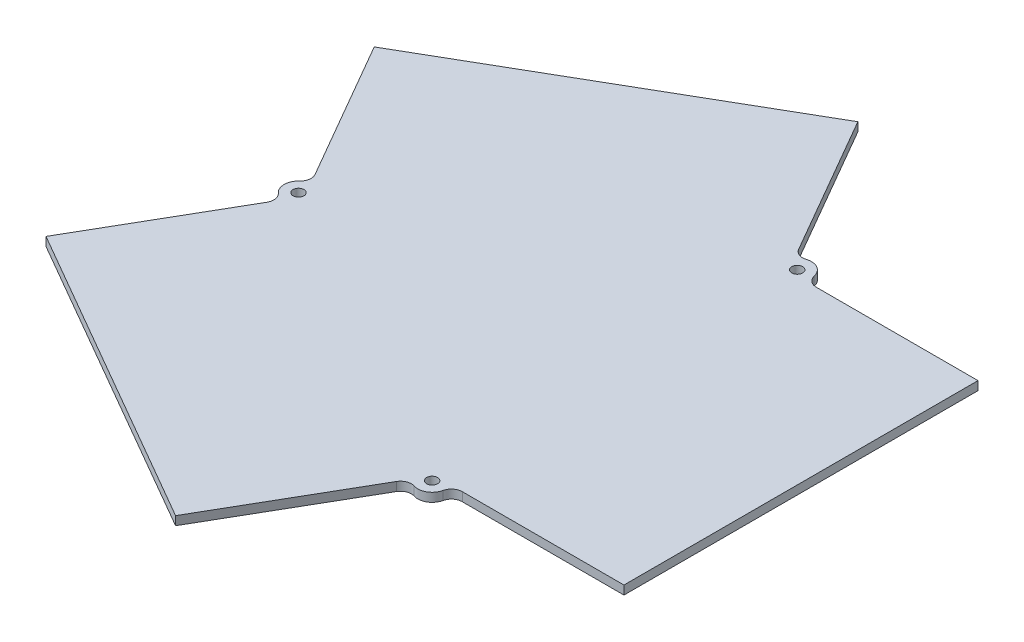
SolidWorks part; units mm, degrees
material "Acrylic (Medium-high impact)"
ref_plane "Front Plane" through (0, 0, 0) normal (0, 0, 1) x (1, 0, 0)
ref_plane "Top Plane" through (0, 0, 0) normal (0, 1, 0) x (1, 0, 0)
ref_plane "Right Plane" through (0, 0, 0) normal (1, 0, 0) x (0, 0, -1)
sketch "Sketch1" plane through (0, 0, 0) normal (0, 1, 0) x (1, 0, 0)
  line L0 (-80.9213, 31.2483) -> (-101.2337, 66.4304)
  line L1 (-103.9658, 67.1624) -> (-33.8177, 107.6624)
  line L2 (-33.8177, 107.6624) -> (-14.0109, 73.356)
  line L4 (-8.3973, 70.115) -> (31.2163, 70.115)
  line L5 (31.2163, 70.115) -> (31.2163, -10.885)
  line L6 (31.2163, -10.885) -> (-8.3973, -10.885)
  line L8 (-14.0109, -14.126) -> (-33.8177, -48.4324)
  line L9 (-33.8177, -48.4324) -> (-103.9658, -7.9324)
  line L10 (-103.9658, -7.9324) -> (-84.1589, 26.374)
  line L12 (-84.1589, 32.856) -> (-103.9658, 67.1624)
  line L13 (-101.2337, 66.4304) -> (-34.5498, 104.9304)
  line L14 (-34.5498, 104.9304) -> (-14.2374, 69.7483)
  line L15 (-11.4084, 68.115) -> (29.2163, 68.115)
  line L16 (29.2163, 68.115) -> (29.2163, -8.885)
  line L17 (29.2163, -8.885) -> (-11.4084, -8.885)
  line L18 (-14.2374, -10.5183) -> (-34.5498, -45.7004)
  line L19 (-34.5498, -45.7004) -> (-101.2337, -7.2004)
  line L20 (-101.2337, -7.2004) -> (-80.9213, 27.9817)
  circle A0 centre (-83.7504, 29.615) radius 1.25
  circle A1 centre (-11.4084, 71.3817) radius 1.25
  circle A2 centre (-11.4084, -12.1517) radius 1.25
  arc A3 (-80.9213, 27.9817) -> (-80.9213, 31.2483) centre (-83.7504, 29.615) ccw
  arc A4 (-8.3973, 70.115) -> (-14.0109, 73.356) centre (-11.4084, 71.3817) ccw
  arc A5 (-11.4084, -8.885) -> (-14.2374, -10.5183) centre (-11.4084, -12.1517) ccw
  arc A6 (-14.0109, -14.126) -> (-8.3973, -10.885) centre (-11.4084, -12.1517) ccw
  arc A7 (-84.1589, 32.856) -> (-84.1589, 26.374) centre (-83.7504, 29.615) ccw
  arc A8 (-14.2374, 69.7483) -> (-11.4084, 68.115) centre (-11.4084, 71.3817) ccw
extrude "Boss-Extrude1" add sketch "Sketch1" along normal blind 2
fillet "Fillet1" radius 2.5 6 edges at (-14.0109, 1, -73.356) (-8.3973, 1, -70.115) (-14.0109, 1, 14.126) (-8.3973, 1, 10.885) (-84.1589, 1, -26.374) (-84.1589, 1, -32.856)
